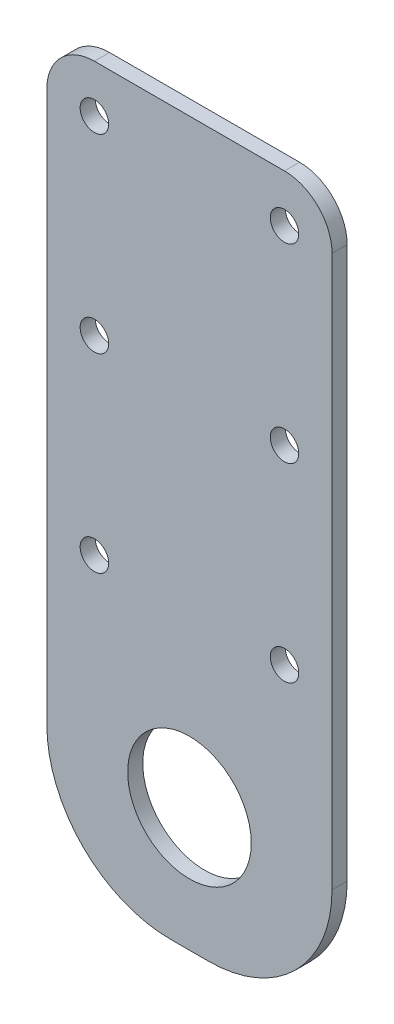
SolidWorks part; units mm, degrees
material "6061 Alloy"
ref_plane "Front Plane" through (0, 0, 0) normal (0, 0, 1) x (1, 0, 0)
ref_plane "Top Plane" through (0, 0, 0) normal (0, 1, 0) x (1, 0, 0)
ref_plane "Right Plane" through (0, 0, 0) normal (1, 0, 0) x (0, 0, -1)
sketch "Sketch1" plane through (0, 0, 0) normal (0, 0, 1) x (1, 0, 0)
  line L0 (0, 0) -> (0, 50)
  line L1 (0, 50) -> (30, 50)
  line L2 (30, 50) -> (30, 0)
  line L6 (0, 0) -> (30, 0) construction
  line L7 (5, 50) -> (5, 0) construction
  line L8 (0, 0) -> (5, 0) construction
  line L9 (5, 45) -> (5, 50) construction
  line L10 (15, 50) -> (15, -13) construction
  line L11 (0, 0) -> (0, -26)
  line L12 (0, -26) -> (30, -26)
  line L13 (0, 25) -> (5, 25) construction
  line L14 (30, -26) -> (30, 0)
  line L15 (15, -13) -> (15, 5) construction
  line L16 (15, 5) -> (25, 5) construction
  circle A0 centre (15, -13) radius 6.5
  circle A1 centre (5, 45) radius 1.5
  circle A2 centre (5, 25) radius 1.5
  circle A3 centre (5, 5) radius 1.5
  circle A4 centre (25, 5) radius 1.5
  circle A5 centre (25, 25) radius 1.5
  circle A6 centre (25, 45) radius 1.5
  dimension "D5" = 13
  dimension "D7" = 3
  dimension "D9" = 20
  dimension "D10" = 20
  dimension "D1" = 30
  dimension "D2" = 50
  dimension "D3" = 13
  dimension "D4" = 13
  dimension "D6" = 5
  dimension "D8" = 5
extrude "Boss-Extrude1" add sketch "Sketch1" along normal blind 1.5875
fillet "Fillet1" radius 5 2 edges at (0, 50, 0.7937) (30, 50, 0.7937)
fillet "Fillet2" radius 13 2 edges at (30, -26, 0.7937) (0, -26, 0.7937)
